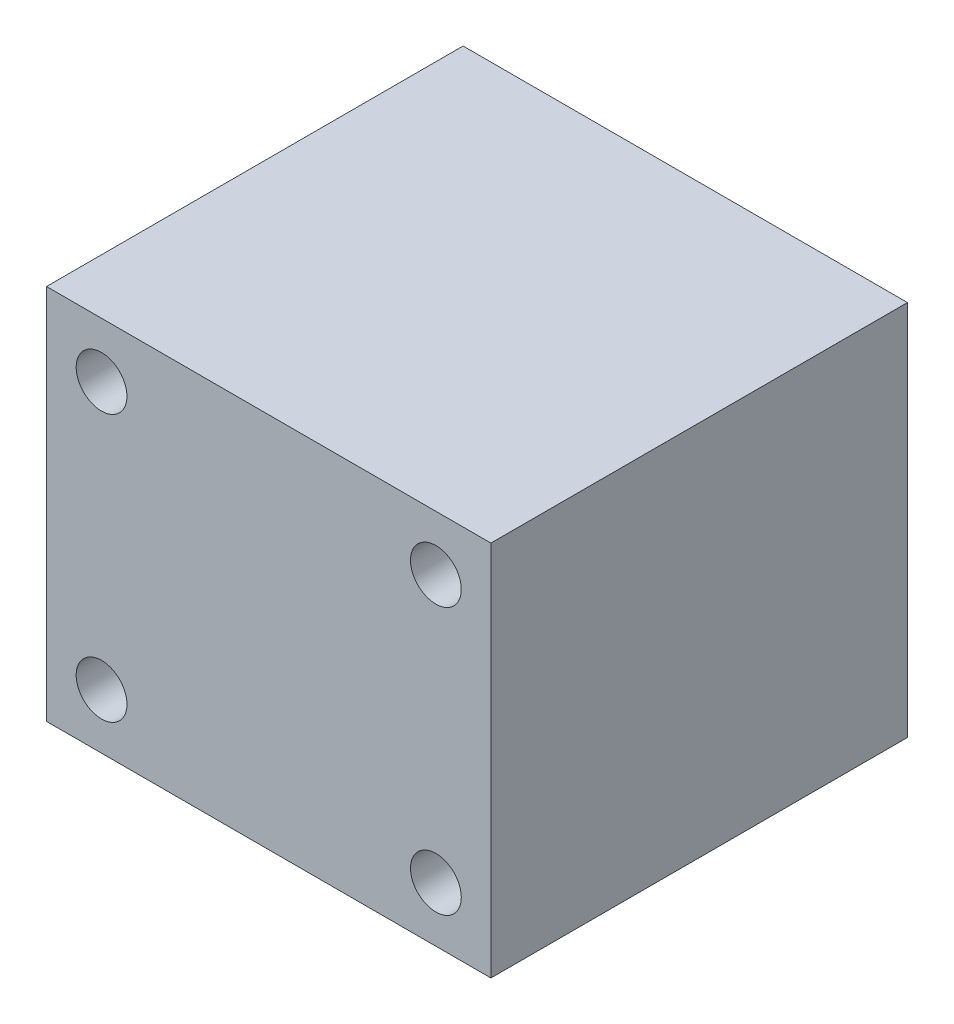
SolidWorks part; units mm, degrees
ref_plane "Front Plane" through (0, 0, 0) normal (0, 0, 1) x (1, 0, 0)
ref_plane "Top Plane" through (0, 0, 0) normal (0, 1, 0) x (1, 0, 0)
ref_plane "Right Plane" through (0, 0, 0) normal (1, 0, 0) x (0, 0, -1)
sketch "Sketch1" plane through (0, 0, 0) normal (0, 0, 1) x (1, 0, 0)
  line L1 (13.335, -11.303) -> (-13.335, -11.303)
  line L2 (13.335, -11.303) -> (13.335, 11.303)
  line L3 (13.335, 11.303) -> (-13.335, 11.303)
  line L4 (-13.335, -11.303) -> (-13.335, 11.303)
  line L5 (13.335, -11.303) -> (-13.335, 11.303) construction
  line L6 (13.335, 11.303) -> (-13.335, -11.303) construction
  line L9 (-21.038, 0) -> (22.2625, 0) construction
  circle A4 centre (10.033, -8.001) radius 1.524
  circle A5 centre (10.033, 8.001) radius 1.524
  circle A6 centre (-10.033, 8.001) radius 1.524
  circle A7 centre (-10.033, -8.001) radius 1.524
  point P0 (0, 0)
  dimension "D6" = 16.002
  dimension "D7" = 3.048
  dimension "D8" = 3.048
  dimension "D10" = 3.048
  dimension "D3" = 3.302
  dimension "D4" = 3.302
  dimension "D5" = 16.002
  dimension "D1" = 22.606
  dimension "D2" = 26.67
extrude "Boss-Extrude2" add sketch "Sketch1" along normal blind 25
